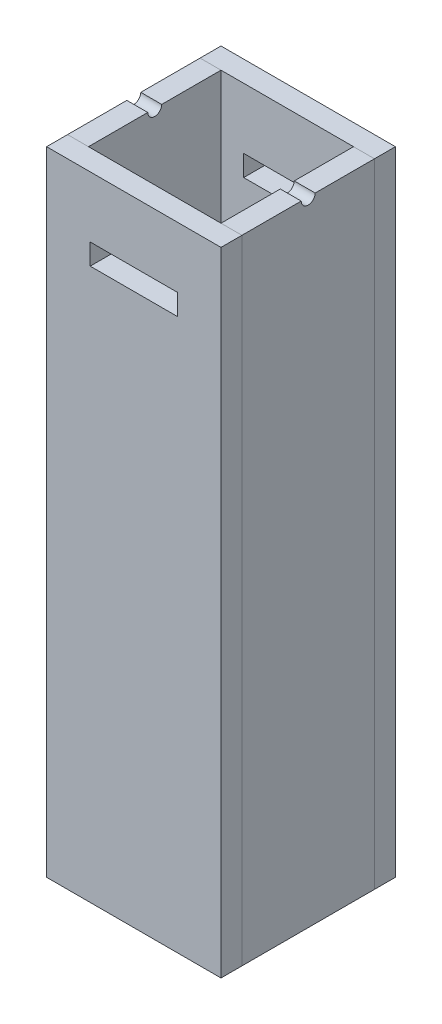
SolidWorks part; units mm, degrees
ref_plane "Plano frontal" through (0, 0, 0) normal (0, 0, 1) x (1, 0, 0)
ref_plane "Plano superior" through (0, 0, 0) normal (0, 1, 0) x (1, 0, 0)
ref_plane "Plano direito" through (0, 0, 0) normal (1, 0, 0) x (0, 0, -1)
sketch "chao" plane through (0, 0, 0) normal (0, 1, 0) x (1, 0, 0)
  line L0 (-124.442, 0) -> (116.8276, 0) construction
sketch "Esboço1" plane through (0, 0, 0) normal (0, 1, 0) x (1, 0, 0)
  line L2 (-27.4557, 25) -> (-27.4557, 19)
  line L6 (-27.4557, -19) -> (-27.4557, -25)
  line L8 (-27.4557, 25) -> (22.5443, 25)
  line L9 (22.5443, 25) -> (22.5443, 19)
  line L10 (22.5443, 19) -> (-27.4557, 19)
  line L11 (-27.4557, -19) -> (22.5443, -19)
  line L12 (22.5443, -19) -> (22.5443, -25)
  line L13 (22.5443, -25) -> (-27.4557, -25)
extrude "parede_1" add sketch "Esboço1" along normal blind 181.4148
sketch "alt_max" plane through (0, 0, 0) normal (0, 0, 1) x (1, 0, 0)
  line L0 (116.8276, 0) -> (116.8276, 230) construction
sketch "Esboço4" plane through (0, 0, -19) normal (0, 0, 1) x (1, 0, 0)
  line L0 (22.5443, 181.4148) -> (16.5443, 181.4148)
  line L1 (-27.4557, 181.4148) -> (22.5443, 181.4148) construction
  line L2 (16.5443, 181.4148) -> (16.5443, 0)
  line L3 (-27.4557, 0) -> (22.5443, 0) construction
  line L4 (16.5443, 0) -> (22.5443, 0)
  line L5 (22.5443, 181.4148) -> (22.5443, 0)
  line L6 (-27.4557, 181.4148) -> (-21.4557, 181.4148)
  line L7 (-21.4557, 181.4148) -> (-21.4557, 0)
  line L8 (-21.4557, 0) -> (-27.4557, 0)
  line L9 (-27.4557, 0) -> (-27.4557, 181.4148)
extrude "parede_2" add sketch "Esboço4" along normal up to surface (38 mm away) separate body up to face at (-2.4557, 90.7074, 19)
sketch "Esboço5" plane through (22.5443, 0, 0) normal (1, 0, 0) x (0, 0, -1)
  line L2 (-19, 181.4148) -> (19, 181.4148) construction
  circle A0 centre (0, 181.4148) radius 2
extrude "Corte_tubo" cut sketch "Esboço5" against normal up to surface (50 mm away)
sketch "Esboço6" plane through (0, 0, 0) normal (0, 0, 1) x (1, 0, 0)
  line L0 (116.8276, 0) -> (116.8276, 30) construction
  line L1 (116.8276, 0) -> (116.8276, 230) construction
  point P5 (0, 0)
sketch "Esboço7" plane through (0, 0, 25) normal (0, 0, 1) x (1, 0, 0)
  line L0 (10.0443, 164) -> (10.0443, 158)
  line L2 (-14.9557, 164) -> (10.0443, 164)
  line L3 (10.0443, 158) -> (-14.9557, 158)
  line L4 (-14.9557, 158) -> (-14.9557, 164)
extrude "Corte-extrusão1" cut sketch "Esboço7" against normal up to surface (50 mm away)
